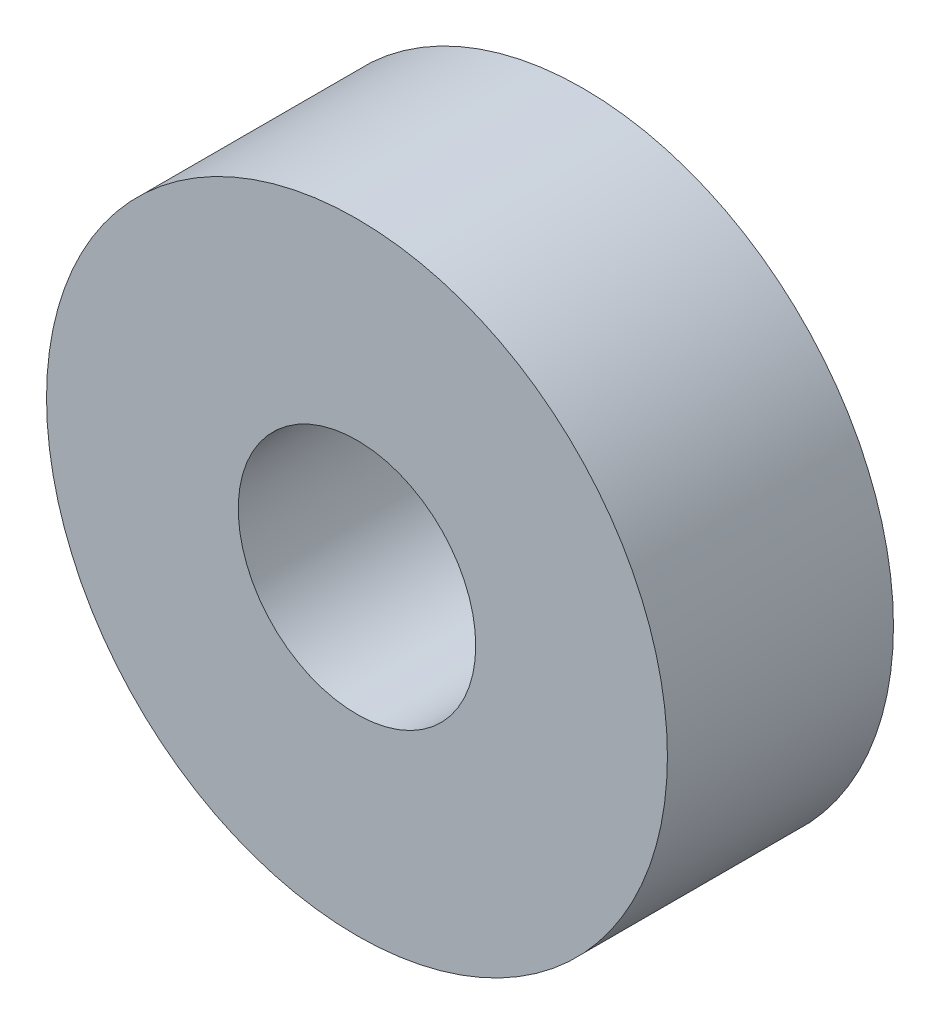
SolidWorks part; units mm, degrees
ref_plane "Front Plane" through (0, 0, 0) normal (0, 0, 1) x (1, 0, 0)
ref_plane "Top Plane" through (0, 0, 0) normal (0, 1, 0) x (1, 0, 0)
ref_plane "Right Plane" through (0, 0, 0) normal (1, 0, 0) x (0, 0, -1)
sketch "Sketch1" plane through (0, 0, 0) normal (0, 0, 1) x (1, 0, 0)
  circle A0 centre (0, 0) radius 10.85
  circle A1 centre (0, 0) radius 4.15
  dimension "D1" = 21.7
  dimension "D2" = 8.3
extrude "Boss-Extrude1" add sketch "Sketch1" along normal blind 7.9
